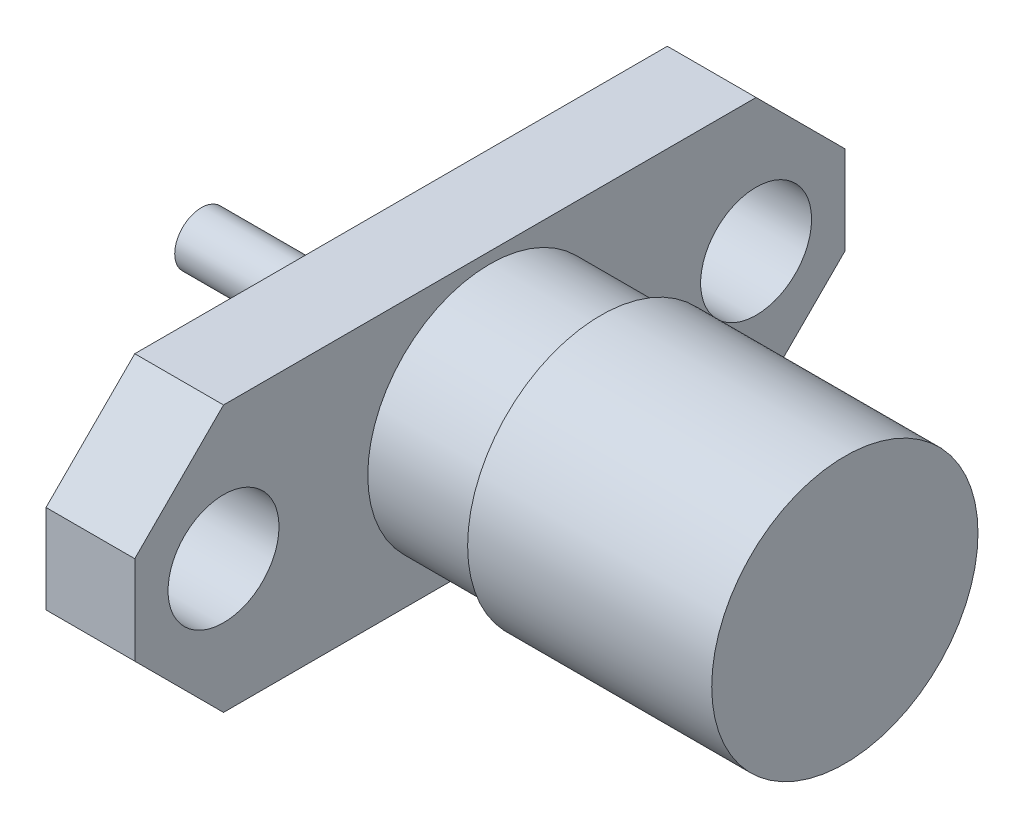
SolidWorks part; units mm, degrees
ref_plane "Спереди" through (0, 0, 0) normal (0, 0, 1) x (1, 0, 0)
ref_plane "Сверху" through (0, 0, 0) normal (0, 1, 0) x (1, 0, 0)
ref_plane "Справа" through (0, 0, 0) normal (1, 0, 0) x (0, 0, -1)
sketch "Эскиз1" plane through (0, 0, 0) normal (1, 0, 0) x (0, 0, -1)
  line L0 (0, -172.7666) -> (0, 8465.5612) construction
  line L1 (-172.7666, 0) -> (8465.5612, 0) construction
  line L2 (-8, 1) -> (-6, 3)
  line L3 (-8, -3) -> (8, -3)
  line L4 (-8, -3) -> (-8, 3)
  line L5 (-8, 3) -> (8, 3)
  line L6 (8, -3) -> (8, 3)
  line L7 (-8, -3) -> (8, 3) construction
  line L8 (-8, 3) -> (8, -3) construction
  line L9 (-6, -1000) -> (-6, 49000) construction
  line L10 (8, 1) -> (6, 3)
  line L11 (8, -1) -> (6, -3)
  line L12 (-8, -1) -> (-6, -3)
  circle A0 centre (-6, 0) radius 1.25
  circle A1 centre (6, 0) radius 1.25
  point P4 (0, 0)
  point P12 (-6, 3)
  dimension "D3" = 2.5
  dimension "D1" = 6
  dimension "D2" = 16
  dimension "D4" = 6
  dimension "D5" = 45
extrude "Бобышка-Вытянуть1" add sketch "Эскиз1" along normal blind 2 contours L4 L12 L3 L11 L6 L10 L5 L2 A0 A1
sketch "Эскиз2" plane through (0, 0, 0) normal (-1, 0, 0) x (0, 0, 1)
  circle A0 centre (0, 0) radius 2.25
  dimension "D1" = 4.5
extrude "Вырез-Вытянуть1" cut sketch "Эскиз2" against normal blind 0.1
sketch "Эскиз6" plane through (0.1, 0, 0) normal (-1, 0, 0) x (0, 0, 1)
  circle A0 centre (0, 0) radius 0.6
  dimension "D1" = 1.2
extrude "Бобышка-Вытянуть2" add sketch "Эскиз6" along normal blind 4.6
sketch "Эскиз7" plane through (2, 0, 0) normal (1, 0, 0) x (0, 0, -1)
  circle A0 centre (0, 0) radius 3
  dimension "D1" = 6
extrude "Бобышка-Вытянуть3" add sketch "Эскиз7" along normal blind 8
sketch "Эскиз8" plane through (0, 0, 0) normal (0, 0, 1) x (1, 0, 0)
  line L0 (0, -3) -> (0, -1) construction
  line L1 (2, -1) -> (2, -3) construction
  line L2 (2, -3) -> (0, -3) construction
  line L3 (0, -1) -> (0, 1) construction
  line L4 (2, 1) -> (2, -1) construction
  line L5 (0, 1) -> (0, 3) construction
  line L6 (0, 3) -> (2, 3) construction
  line L7 (2, 3) -> (2, 1) construction
  line L8 (0, -3) -> (0, -1)
  line L9 (2, -1) -> (2, -3)
  line L10 (2, -3) -> (0, -3)
  line L11 (0, -1) -> (0, 1)
  line L12 (2, 1) -> (2, -1)
  line L13 (0, 1) -> (0, 3)
  line L14 (0, 3) -> (2, 3)
  line L15 (2, 3) -> (2, 1)
  line L16 (-1000, 0) -> (49000, 0) construction
  line L17 (2, 3) -> (4.5, 3)
  line L18 (2, 3) -> (2, 2.75)
  line L19 (2, 2.75) -> (4.5, 2.75)
  line L20 (4.5, 3) -> (4.5, 2.75)
  dimension "D1" = 2.5
  dimension "D2" = 2.75
revolve "Вырез-Повернуть1" cut sketch "Эскиз8" angle 360 about L16
